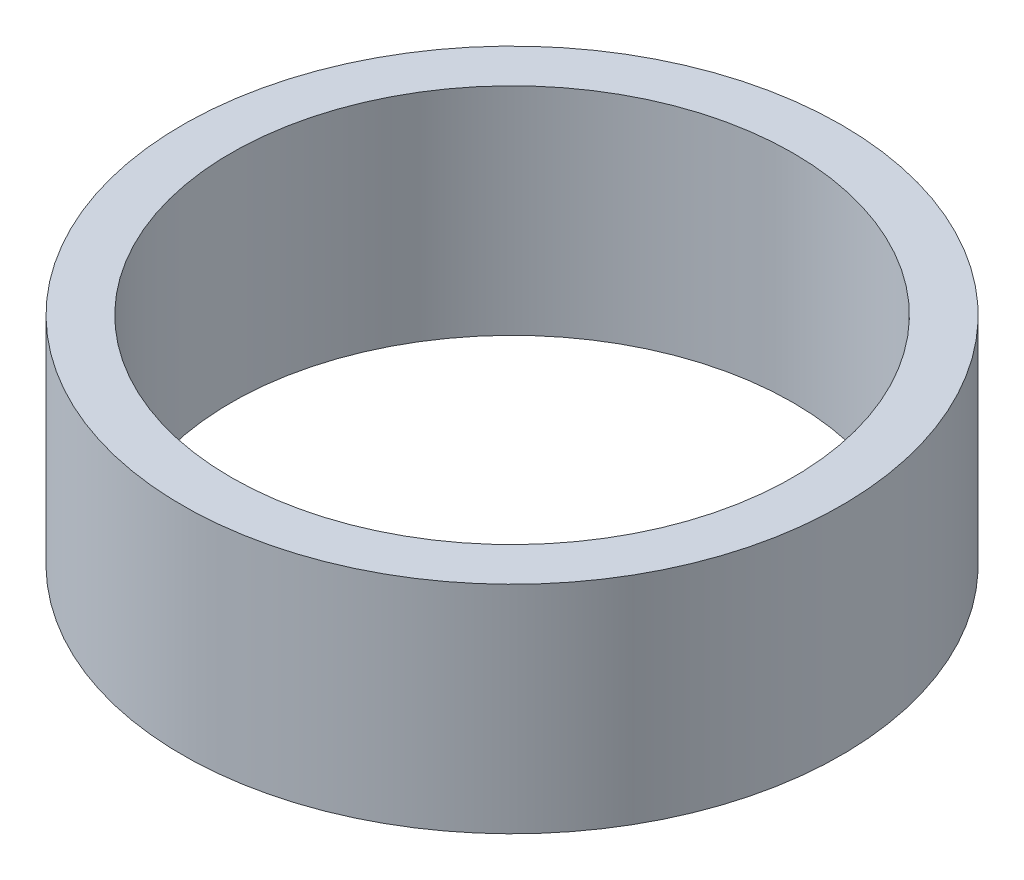
SolidWorks part; units mm, degrees
material "AISI 304"
ref_plane "Alzado" through (0, 0, 0) normal (0, 0, 1) x (1, 0, 0)
ref_plane "Planta" through (0, 0, 0) normal (0, 1, 0) x (1, 0, 0)
ref_plane "Vista lateral" through (0, 0, 0) normal (1, 0, 0) x (0, 0, -1)
sketch "Sketch1" plane through (0, 0, 0) normal (0, 0, 1) x (1, 0, 0)
  line L0 (10.4, -4) -> (12.2, -4)
  line L1 (12.2, -4) -> (12.2, 4)
  line L2 (12.2, 4) -> (10.4, 4)
  line L3 (10.4, 4) -> (10.4, -4)
  line L4 (0, -8) -> (0, 8) construction
revolve "Anillo" add sketch "Sketch1" angle 360 about L4
